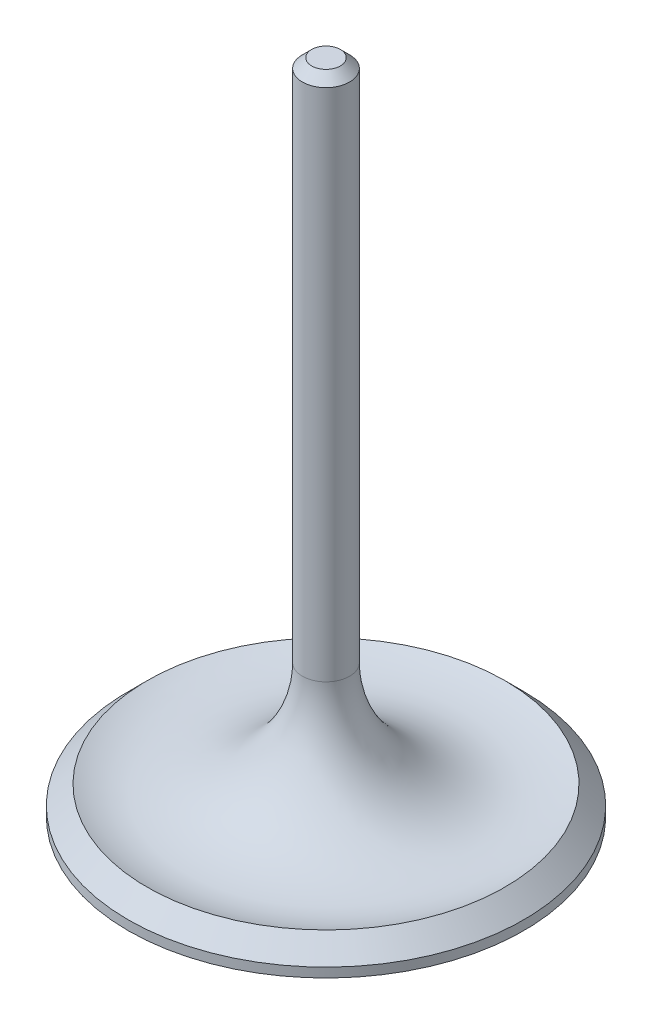
SolidWorks part; units mm, degrees
ref_plane "Front Plane" through (0, 0, 0) normal (0, 0, 1) x (1, 0, 0)
ref_plane "Top Plane" through (0, 0, 0) normal (0, 1, 0) x (1, 0, 0)
ref_plane "Right Plane" through (0, 0, 0) normal (1, 0, 0) x (0, 0, -1)
sketch "Sketch1" plane through (0, 0, 0) normal (1, 0, 0) x (0, 0, -1)
  line L0 (0, 0) -> (0, 88.55)
  line L1 (0, 88.55) -> (3.18, 88.55)
  line L2 (3.18, 88.55) -> (3.18, 17.9627)
  line L3 (24.11, 3.81) -> (26.65, 1.27)
  line L4 (26.65, 1.27) -> (26.65, 0)
  line L5 (26.65, 0) -> (0, 0)
  arc A0 (3.18, 17.9627) -> (24.11, 3.81) centre (18.43, 17.9627) ccw
  dimension "D1" = 88.55
  dimension "D7" = 15.25
  dimension "D2" = 26.65
  dimension "D3" = 1.27
  dimension "D4" = 3.81
  dimension "D5" = 45
  dimension "D6" = 3.18
revolve "Revolve1" add sketch "Sketch1" angle 360 about L0
chamfer "Chamfer1" distance 1.25 angle 45 1 edges at (0, 88.55, -3.18)
